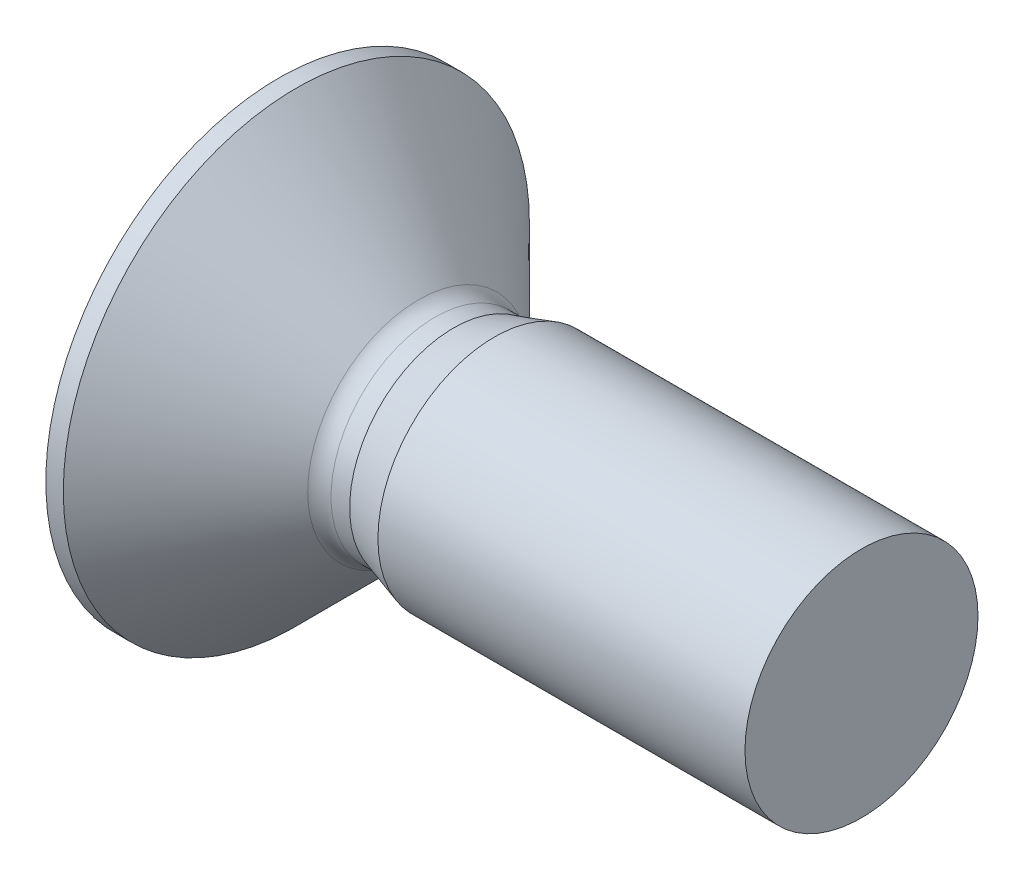
SolidWorks part; units mm, degrees
ref_plane "前基準面" through (0, 0, 0) normal (0, 0, 1) x (1, 0, 0)
ref_plane "上基準面" through (0, 0, 0) normal (0, 1, 0) x (1, 0, 0)
ref_plane "右基準面" through (0, 0, 0) normal (1, 0, 0) x (0, 0, -1)
sketch "草圖1" plane through (0, 0, 0) normal (0, 0, 1) x (1, 0, 0)
  line L0 (-2.3, 4) -> (-2.3, 0)
  line L1 (-2.3, 0) -> (7.7, 0)
  line L2 (7.7, 0) -> (7.7, 2)
  line L3 (7.7, 2) -> (1.4, 2)
  line L4 (1.4, 2) -> (0.7, 1.7853)
  line L5 (0.7, 1.7853) -> (0.2148, 1.7853)
  line L6 (0.2148, 1.7853) -> (-2, 4)
  line L7 (-2, 4) -> (-2.3, 4)
  line L8 (-2.3, 0) -> (7.7, 0) construction
revolve "旋轉1" add sketch "草圖1" angle 360 about L8
sketch "草圖2" plane through (-2.3, 0, 0) normal (-1, 0, 0) x (0, 0, 1)
  line L0 (0.5333, -0.5333) -> (2.25, -0.5333)
  line L1 (2.25, -0.5333) -> (2.25, 0.5333)
  line L2 (2.25, 0.5333) -> (0.5333, 0.5333)
  line L3 (0.5333, 0.5333) -> (0.5333, 2.25)
  line L4 (0.5333, 2.25) -> (-0.5333, 2.25)
  line L5 (-0.5333, 2.25) -> (-0.5333, 0.5333)
  line L6 (-0.5333, 0.5333) -> (-2.25, 0.5333)
  line L7 (-2.25, 0.5333) -> (-2.25, -0.5333)
  line L8 (-2.25, -0.5333) -> (-0.5333, -0.5333)
  line L9 (-0.5333, -0.5333) -> (-0.5333, -2.25)
  line L10 (-0.5333, -2.25) -> (0.5333, -2.25)
  line L11 (0.5333, -2.25) -> (0.5333, -0.5333)
extrude "除料-伸長1" cut sketch "草圖2" against normal blind 1.15
fillet "圓角1" radius 0.4 1 edges at (0.2148, 0, -1.7853)
fillet "圓角2" radius 0.8 4 edges at (-1.725, 0.5333, 0.5333) (-1.725, -0.5333, 0.5333) (-1.725, -0.5333, -0.5333) (-1.725, 0.5333, -0.5333)
